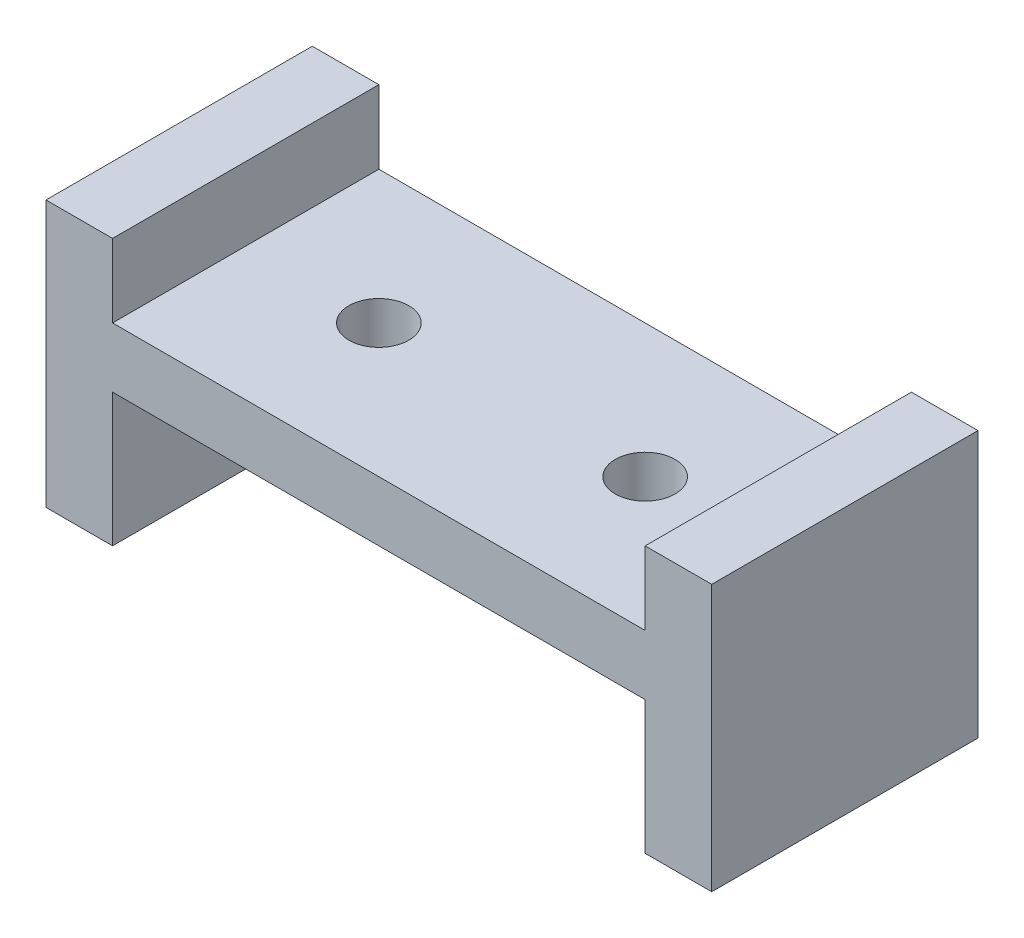
SolidWorks part; units mm, degrees
ref_plane "Alzado" through (0, 0, 0) normal (0, 0, 1) x (1, 0, 0)
ref_plane "Planta" through (0, 0, 0) normal (0, 1, 0) x (1, 0, 0)
ref_plane "Vista lateral" through (0, 0, 0) normal (1, 0, 0) x (0, 0, -1)
sketch "Croquis1" plane through (0, 0, 0) normal (0, 1, 0) x (1, 0, 0)
  line L0 (-35, -175) -> (-45, -175)
  line L1 (-5, -195) -> (-35, -195)
  line L2 (-35, -190) -> (-5, -190) construction
  line L3 (-5, -190) -> (-5, -180) construction
  line L4 (-35, -190) -> (-35, -180) construction
  line L5 (-35, -180) -> (-5, -180) construction
  line L6 (-35, -175) -> (-5, -175)
  line L7 (5, -195) -> (5, -175)
  line L8 (-5, -195) -> (5, -195)
  line L9 (5, -175) -> (-5, -175)
  line L10 (-45, -175) -> (-45, -195)
  line L11 (-45, -195) -> (-35, -195)
  circle A2 centre (-30, -185) radius 2.25
  circle A3 centre (-10, -185) radius 2.25
  dimension "D13" = 4.5
  dimension "D14" = 4.5
  dimension "D9" = 10
  dimension "D10" = 20
extrude "Saliente-Extruir1" add sketch "Croquis1" along normal blind 4.5
sketch "Croquis3" plane through (0, 4.5, 0) normal (0, 1, 0) x (1, 0, 0)
  line L0 (5, -195) -> (5, -175)
  line L1 (5, -175) -> (0, -175)
  line L2 (5, -175) -> (-45, -175) construction
  line L3 (0, -175) -> (0, -195)
  line L4 (-45, -195) -> (5, -195) construction
  line L5 (0, -195) -> (5, -195)
  line L6 (-45, -195) -> (-45, -175)
  line L7 (-45, -175) -> (-40, -175)
  line L8 (-40, -175) -> (-40, -195)
  line L9 (-40, -195) -> (-45, -195)
extrude "Saliente-Extruir3" add sketch "Croquis3" along normal blind 5.5
sketch "Croquis4" plane through (0, 0, 0) normal (0, -1, 0) x (1, 0, 0)
  line L0 (5, 195) -> (5, 175)
  line L1 (5, 175) -> (0, 175)
  line L2 (5, 175) -> (-45, 175) construction
  line L3 (0, 175) -> (0, 195)
  line L4 (0, 195) -> (5, 195)
  line L5 (-45, 195) -> (-40, 195)
  line L6 (-40, 195) -> (-40, 175)
  line L7 (-40, 175) -> (-40.8247, 175)
  line L8 (-45, 175) -> (-45, 195)
  line M1 (-45, 195) -> (-45, 175)
  line M2 (-45, 175) -> (5, 175)
  line M3 (5, 175) -> (5, 195)
  line M4 (5, 195) -> (-45, 195)
extrude "Saliente-Extruir4" add sketch "Croquis4" along normal blind 10 contours L3 M2 M3 M4 | L6 M4 M1 M2
